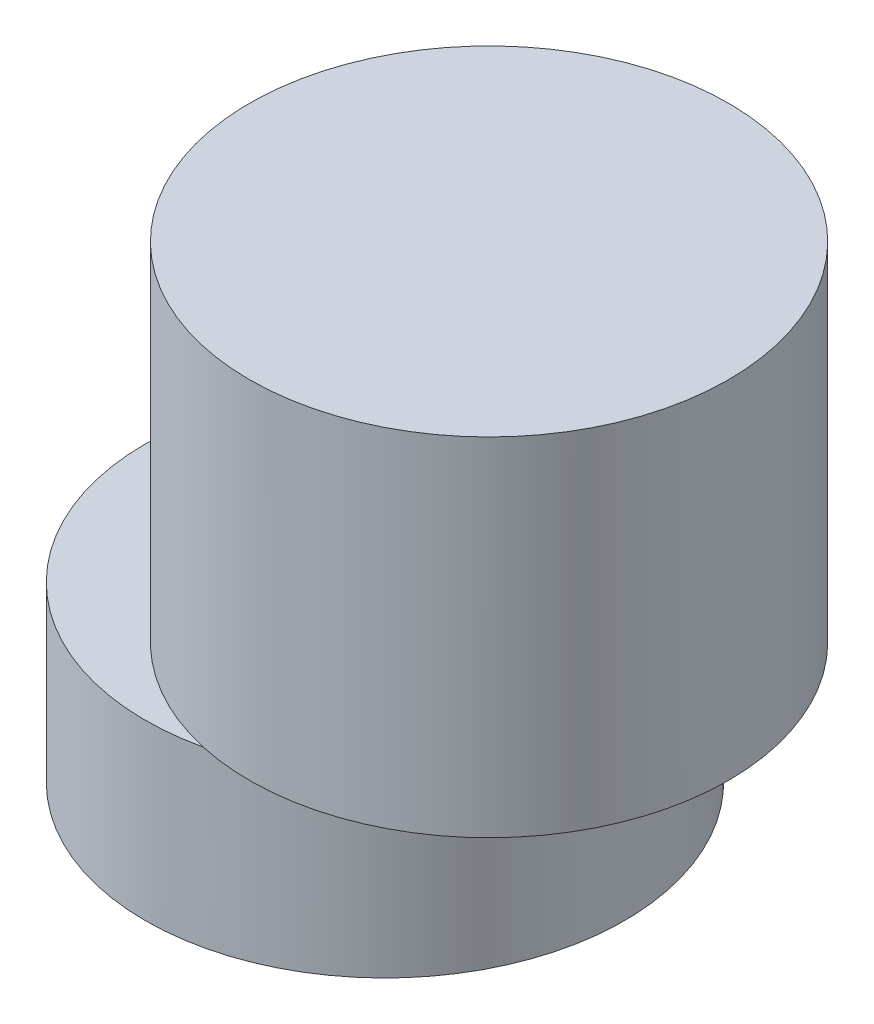
SolidWorks part; units mm, degrees
ref_plane "Front Plane" through (0, 0, 0) normal (0, 0, 1) x (1, 0, 0)
ref_plane "Top Plane" through (0, 0, 0) normal (0, 1, 0) x (1, 0, 0)
ref_plane "Right Plane" through (0, 0, 0) normal (1, 0, 0) x (0, 0, -1)
sketch "Sketch1" plane through (0, 0, 0) normal (0, 1, 0) x (1, 0, 0)
  circle A0 centre (0, 0) radius 3.45
  dimension "D1" = 6.9
extrude "Boss-Extrude1" add sketch "Sketch1" along normal blind 2.5
sketch "Sketch2" plane through (0, 2.5, 0) normal (0, 1, 0) x (1, 0, 0)
  line L0 (0, 0) -> (1.5, 0) construction
  circle A0 centre (1.5, 0) radius 3.45
  dimension "D2" = 6.9
  dimension "D1" = 1.5
extrude "Boss-Extrude2" add sketch "Sketch2" along normal blind 5
sketch "Sketch3" plane through (0, 0, 0) normal (0, -1, 0) x (1, 0, 0)
  arc A0 (0.75, -3.3675) -> (0.75, 3.3675) centre (1.5, 0) ccw construction
  arc A1 (0.75, 3.3675) -> (0.75, -3.3675) centre (1.5, 0) ccw construction
  arc A2 (0.75, -3.3675) -> (0.75, 3.3675) centre (1.5, 0) ccw
  arc A3 (0.75, 3.3675) -> (0.75, -3.3675) centre (1.5, 0) ccw
